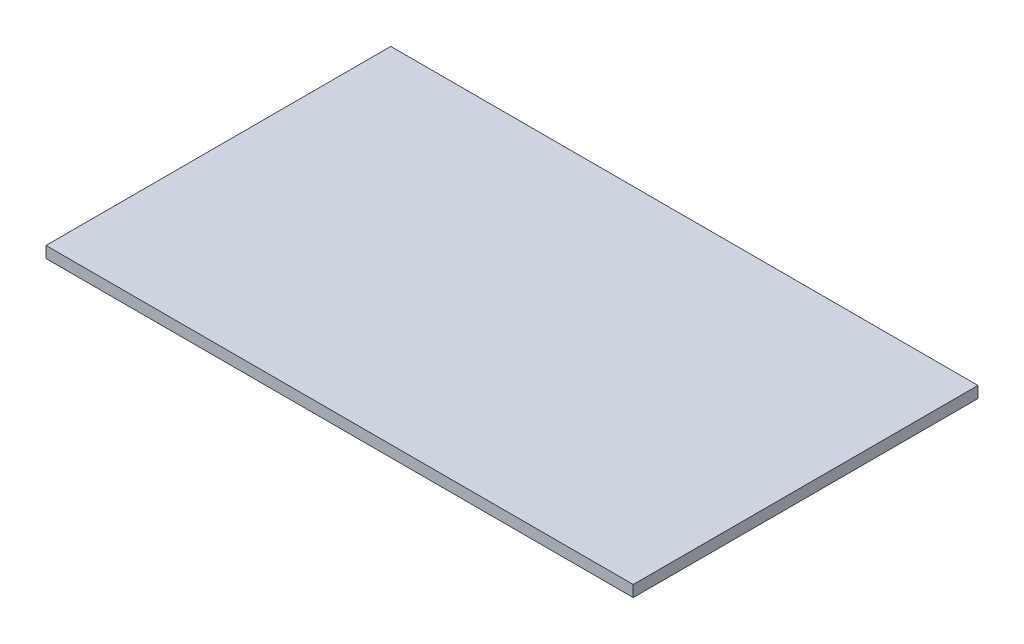
SolidWorks part; units mm, degrees
ref_plane "Front Plane" through (0, 0, 0) normal (0, 0, 1) x (1, 0, 0)
ref_plane "Top Plane" through (0, 0, 0) normal (0, 1, 0) x (1, 0, 0)
ref_plane "Right Plane" through (0, 0, 0) normal (1, 0, 0) x (0, 0, -1)
sketch "Sketch1" plane through (0, 0, 0) normal (0, 1, 0) x (1, 0, 0)
  line L1 (0, 0) -> (984.25, 0)
  line L2 (0, 0) -> (0, 577.85)
  line L3 (0, 577.85) -> (984.25, 577.85)
  line L4 (984.25, 0) -> (984.25, 577.85)
  dimension "D1" = 577.85
  dimension "D2" = 984.25
extrude "Boss-Extrude1" add sketch "Sketch1" along normal blind 19.05
